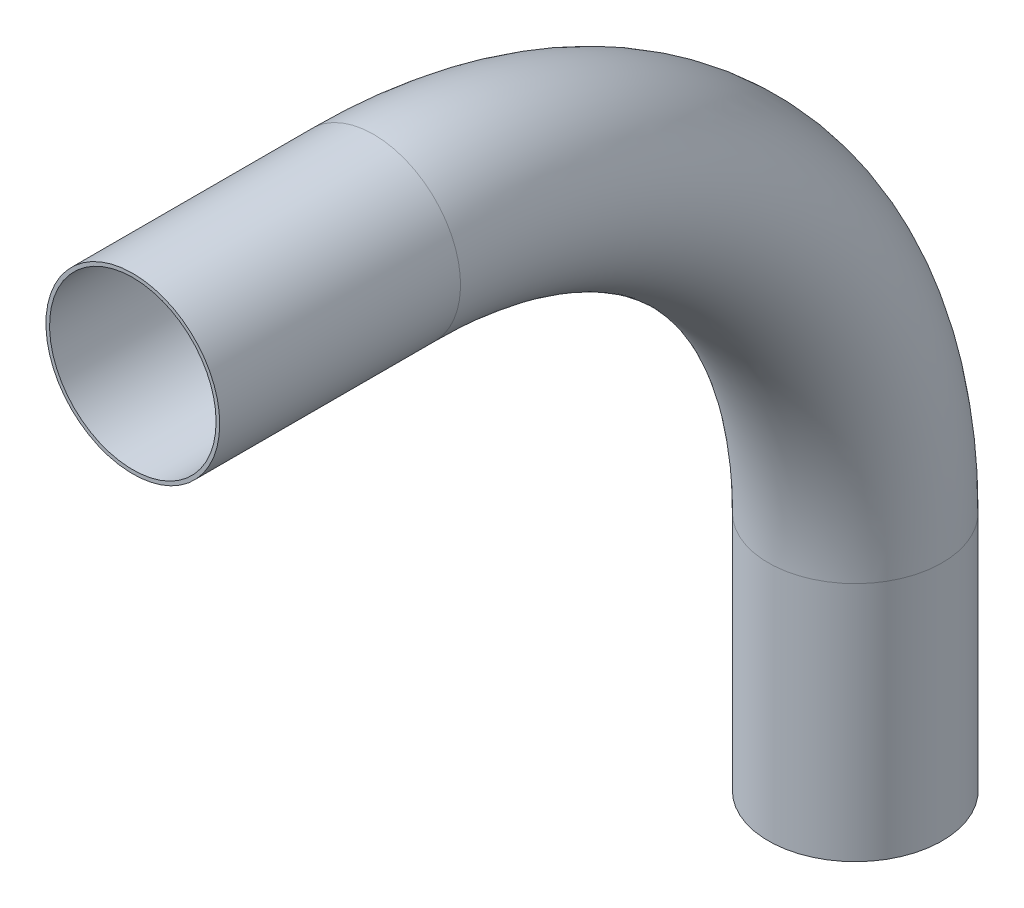
SolidWorks part; units mm, degrees
ref_plane "Front Plane" through (0, 0, 0) normal (0, 0, 1) x (1, 0, 0)
ref_plane "Top Plane" through (0, 0, 0) normal (0, 1, 0) x (1, 0, 0)
ref_plane "Right Plane" through (0, 0, 0) normal (1, 0, 0) x (0, 0, -1)
ref_plane "Plane1"
sketch "Sketch1" plane through (0, 0, 0) normal (0, 1, 0) x (-1, 0, 0)
  circle A0 centre (0, 0) radius 55
  circle A1 centre (0, 0) radius 52.7
  dimension "D1" = 110
extrude "Extrusion1" add sketch "Sketch1" along normal blind 152.4 contours A0 A1
ref_plane "Plane2"
sketch "Sketch2" plane through (0, 152.4, 0) normal (0, 1, 0) x (1, 0, 0)
  circle A0 centre (0, 0) radius 55
  circle A1 centre (0, 0) radius 52.7
ref_plane "Plane3"
sketch "Sketch3" plane through (-55, 152.4, 0) normal (-1, 0, 0) x (0, -1, 0)
  arc A0 (-304.8, 304.8) -> (0, 0) centre (0, 304.8) ccw
  dimension "D1" = 304.8
sweep "Sweep1" add profiles "Sketch2" path "Sketch3"
ref_plane "Plane4"
sketch "Sketch4" plane through (0, 457.2, 304.8) normal (0, 0, 1) x (1, 0, 0)
  circle A0 centre (0, 0) radius 55
  circle A1 centre (0, 0) radius 52.7
extrude "Extrusion2" add sketch "Sketch4" along normal blind 152.4 contours A0 A1
